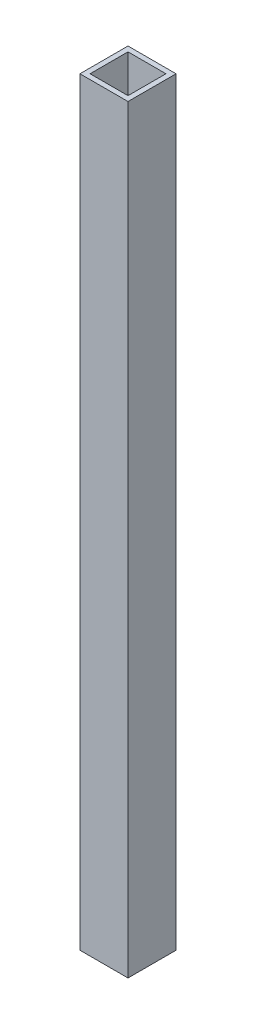
SolidWorks part; units mm, degrees
ref_plane "Front Plane" through (0, 0, 0) normal (0, 0, 1) x (1, 0, 0)
ref_plane "Top Plane" through (0, 0, 0) normal (0, 1, 0) x (1, 0, 0)
ref_plane "Right Plane" through (0, 0, 0) normal (1, 0, 0) x (0, 0, -1)
sketch "Sketch1" plane through (0, 0, 0) normal (0, 1, 0) x (1, 0, 0)
  line L0 (-7.5, 7.5) -> (7.5, 7.5)
  line L1 (-9.5, -9.5) -> (9.5, -9.5)
  line L2 (-9.5, -9.5) -> (-9.5, 9.5)
  line L3 (-9.5, 9.5) -> (9.5, 9.5)
  line L4 (9.5, -9.5) -> (9.5, 9.5)
  line L5 (-9.5, -9.5) -> (9.5, 9.5) construction
  line L6 (-9.5, 9.5) -> (9.5, -9.5) construction
  line L7 (7.5, -7.5) -> (7.5, 7.5)
  line L8 (-7.5, -7.5) -> (7.5, -7.5)
  line L9 (-7.5, -7.5) -> (-7.5, 7.5)
  point P0 (0, 0)
  dimension "D1" = 19
  dimension "D2" = 19
  dimension "D3" = 2
extrude "Boss-Extrude1" add sketch "Sketch1" along normal blind 300
